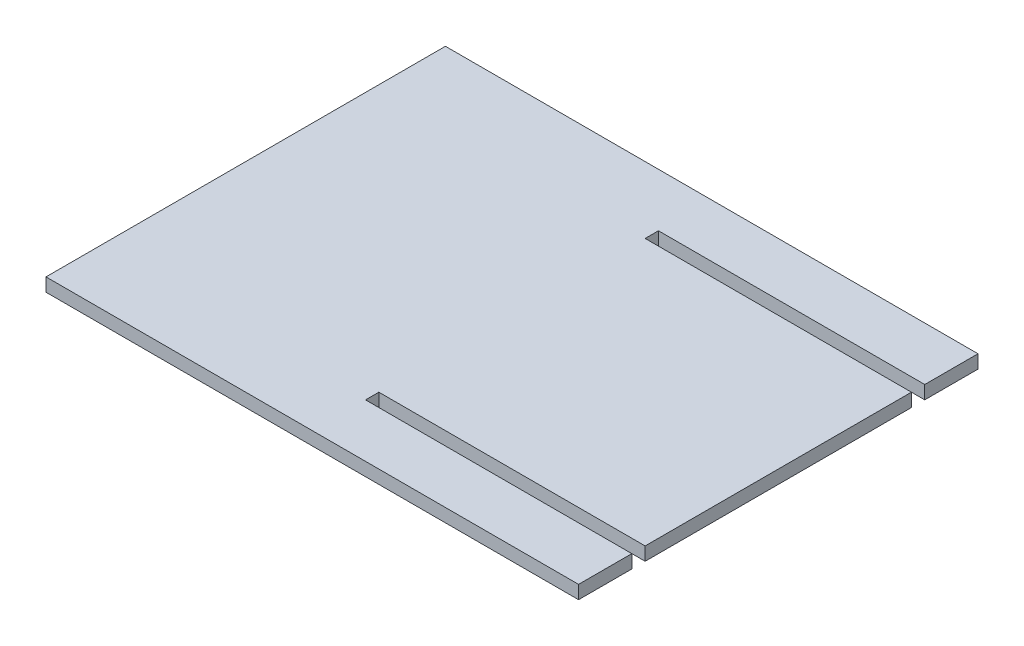
SolidWorks part; units mm, degrees
ref_plane "Front Plane" through (0, 0, 0) normal (0, 0, 1) x (1, 0, 0)
ref_plane "Top Plane" through (0, 0, 0) normal (0, 1, 0) x (1, 0, 0)
ref_plane "Right Plane" through (0, 0, 0) normal (1, 0, 0) x (0, 0, -1)
sketch "Sketch1" plane through (0, 0, 0) normal (0, 1, 0) x (1, 0, 0)
  line L0 (60, 30) -> (0, 30)
  line L1 (-60, -45) -> (60, -45)
  line L2 (-60, -45) -> (-60, 45)
  line L3 (-60, 45) -> (60, 45)
  line L4 (60, -45) -> (60, 45)
  line L5 (-60, -45) -> (60, 45) construction
  line L6 (-60, 45) -> (60, -45) construction
  line L7 (0, 30) -> (0, 33)
  line L8 (0, 33) -> (60, 33)
  line L9 (-55, 0) -> (55, 0) construction
  line L10 (60, -30) -> (0, -30)
  line L11 (0, -30) -> (0, -33)
  line L12 (0, -33) -> (60, -33)
  point P0 (0, 0)
  dimension "D1" = 90
  dimension "D2" = 120
  dimension "D3" = 3
  dimension "D4" = 30
extrude "Boss-Extrude2" add sketch "Sketch1" along normal blind 3 contours L12 L11 L10 L4 L0 L7 L8 L3 L2 L1
